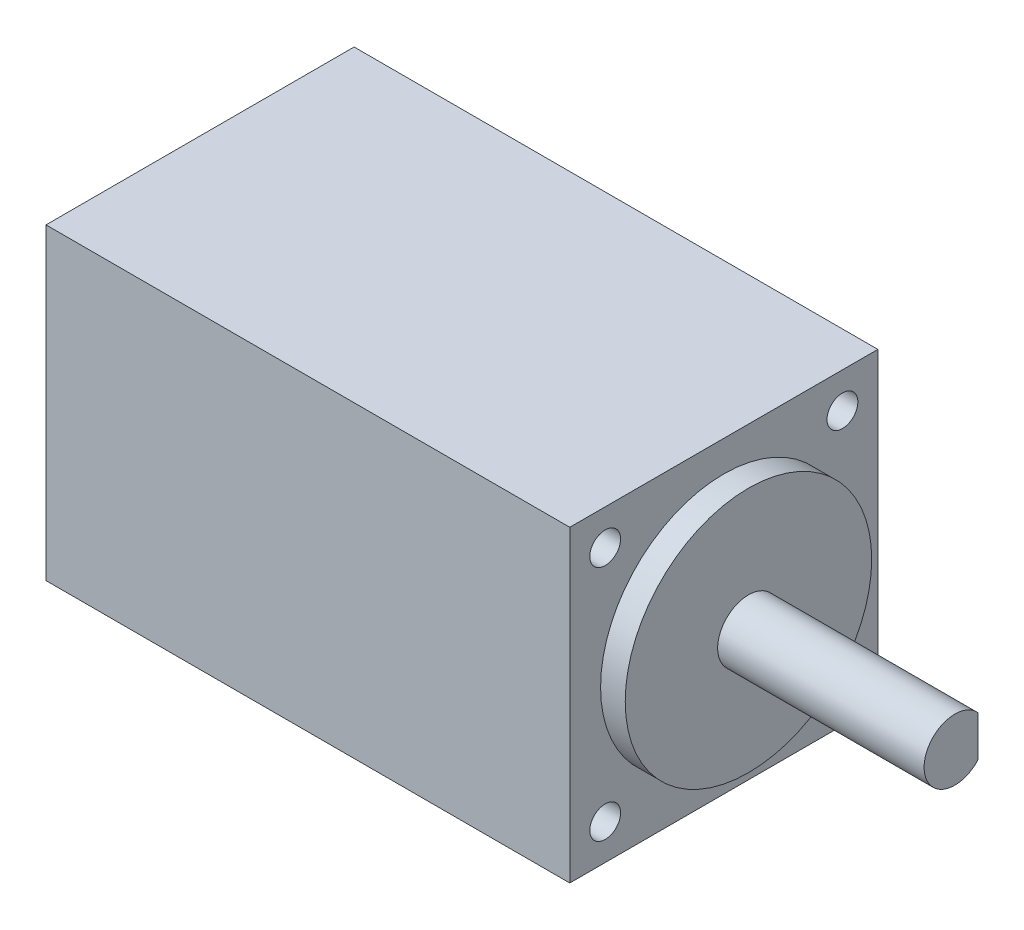
SolidWorks part; units mm, degrees
ref_plane "前视基准面" through (0, 0, 0) normal (0, 0, 1) x (1, 0, 0)
ref_plane "上视基准面" through (0, 0, 0) normal (0, 1, 0) x (1, 0, 0)
ref_plane "右视基准面" through (0, 0, 0) normal (1, 0, 0) x (0, 0, -1)
sketch "草图1" plane through (0, 0, 0) normal (1, 0, 0) x (0, 0, -1)
  line L1 (0, 0) -> (20, 0)
  line L2 (0, 0) -> (0, 20)
  line L3 (0, 20) -> (20, 20)
  line L4 (20, 0) -> (20, 20)
  circle A0 centre (2.3, 2.3) radius 1
  circle A1 centre (2.3, 17.7) radius 1
  circle A2 centre (17.7, 17.7) radius 1
  circle A3 centre (17.7, 2.2986) radius 1
extrude "凸台-拉伸2" add sketch "草图1" along normal blind 34
sketch "草图2" plane through (34, 0, 0) normal (1, 0, 0) x (0, 0, -1)
  circle A0 centre (10, 10) radius 8
extrude "凸台-拉伸3" add sketch "草图2" along normal blind 1.6 contours A0
sketch "草图3" plane through (35.6, 0, 0) normal (1, 0, 0) x (0, 0, -1)
  circle A0 centre (10, 10) radius 2
extrude "凸台-拉伸4" add sketch "草图3" along normal blind 13.4
sketch "草图4" plane through (49, 0, 0) normal (1, 0, 0) x (0, 0, -1)
  line L0 (8, 10) -> (11.5, 10)
  line L1 (11.5, 8.6771) -> (11.5, 11.3229)
  circle A0 centre (10, 10) radius 2 construction
  circle A1 centre (10, 10) radius 2 construction
  circle A2 centre (10, 10) radius 2
  circle M3 centre (10, 10) radius 2
extrude "切除-拉伸1" cut sketch "草图4" against normal blind 9 contours L1 M3
